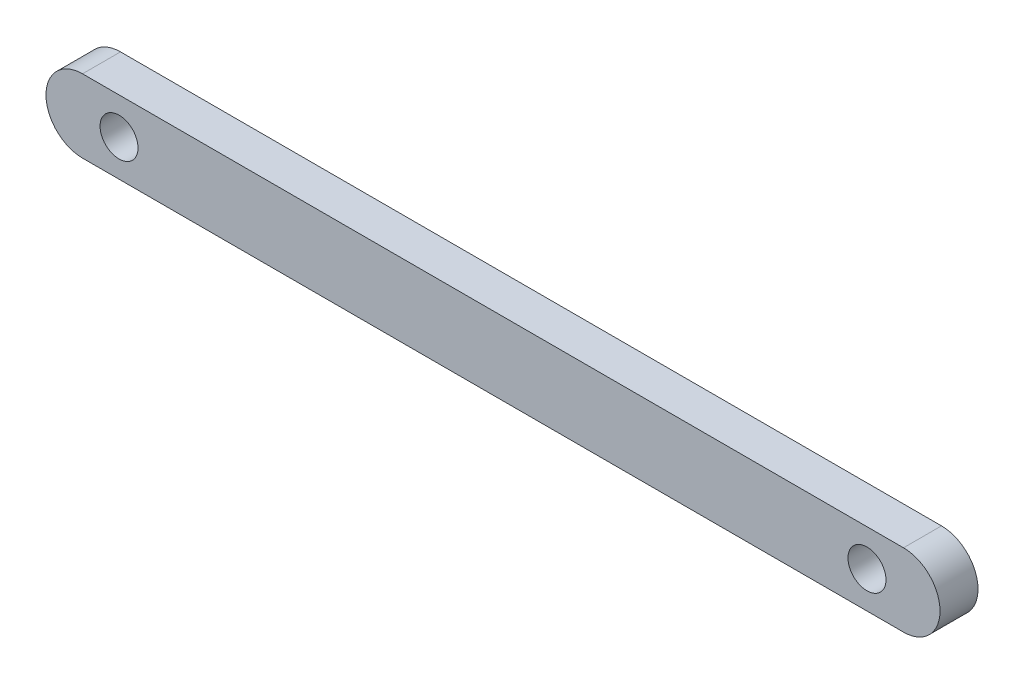
SolidWorks part; units mm, degrees
material "1060 Alloy"
ref_plane "Front Plane" through (0, 0, 0) normal (0, 0, 1) x (1, 0, 0)
ref_plane "Top Plane" through (0, 0, 0) normal (0, 1, 0) x (1, 0, 0)
ref_plane "Right Plane" through (0, 0, 0) normal (1, 0, 0) x (0, 0, -1)
sketch "Sketch1" plane through (0, 0, 0) normal (0, 0, 1) x (1, 0, 0)
  line L0 (-35.687, 0) -> (35.687, 0) construction
  line L1 (-35.687, 3.175) -> (35.687, 3.175)
  line L2 (-35.687, -3.175) -> (35.687, -3.175)
  arc A0 (-35.687, 3.175) -> (-35.687, -3.175) centre (-35.687, 0) ccw
  arc A1 (35.687, -3.175) -> (35.687, 3.175) centre (35.687, 0) ccw
  point P2 (0, 0)
  point P8 (-38.862, 0)
  point P9 (38.862, 0)
  dimension "D1" = 77.724
  dimension "D2" = 6.35
extrude "Boss-Extrude1" add sketch "Sketch1" along normal blind 3.302
hole_wizard "3/8 (0.13) Diameter Hole1" positions "Sketch2" profile "Sketch3" hole size "3/8" standard "ANSI Inch" end condition through all
sketch "Sketch2" plane through (0, 0, 3.302) normal (0, 0, 1) x (1, 0, 0)
  arc A0 (-35.687, 3.175) -> (-35.687, -3.175) centre (-35.687, 0) ccw construction
  arc A1 (35.687, -3.175) -> (35.687, 3.175) centre (35.687, 0) ccw construction
  point P0 (-32.512, 0)
  point P2 (32.512, 0)
  point P8 (-38.862, 0)
  point P14 (38.862, 0)
  dimension "D1" = 6.35
  dimension "D2" = 6.35
sketch "Sketch3" plane through (-32.512, 0, 3.302) normal (1, 0, 0) x (0, -1, 0)
  line L0 (0, 0) -> (0, 3.302)
  line L1 (0, 3.302) -> (1.651, 3.302)
  line L2 (1.651, 3.302) -> (1.651, 0)
  line L5 (1.651, 0) -> (0, 0)
  line L11 (0, -6.35) -> (0, 107.95) construction
  dimension "Thru Hole Dia." = 3.302
  dimension "Thru Hole Depth" = 3.302
